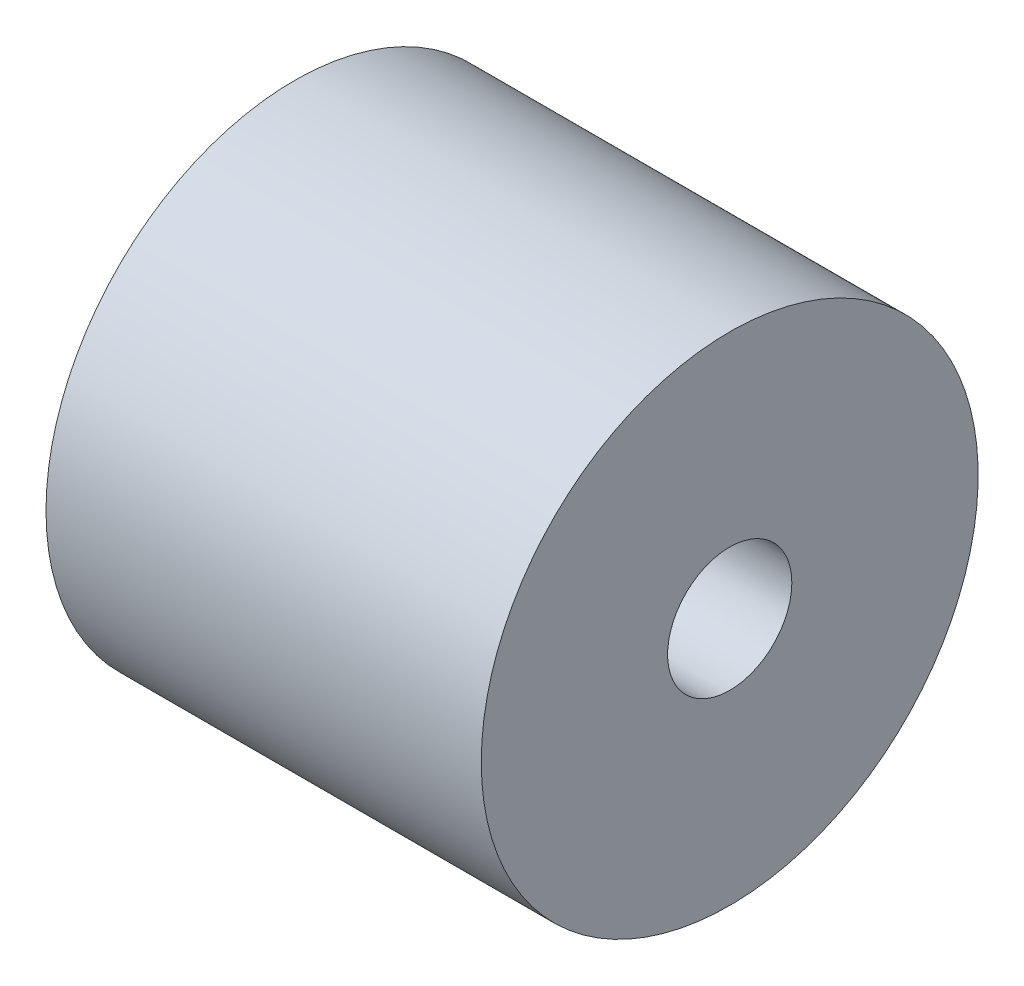
SolidWorks part; units mm, degrees
ref_plane "Front Plane" through (0, 0, 0) normal (0, 0, 1) x (1, 0, 0)
ref_plane "Top Plane" through (0, 0, 0) normal (0, 1, 0) x (1, 0, 0)
ref_plane "Right Plane" through (0, 0, 0) normal (1, 0, 0) x (0, 0, -1)
sketch "Sketch1" plane through (0, 0, 0) normal (1, 0, 0) x (0, 0, -1)
  circle A0 centre (0, 0) radius 3.175
  circle A1 centre (0, 0) radius 6.35
  dimension "D1" = 6.35
  dimension "D2" = 3.175
extrude "Boss-Extrude1" add sketch "Sketch1" along normal blind 11.1252
sketch "Sketch2" plane through (11.1252, 0, 0) normal (1, 0, 0) x (0, 0, -1)
  circle A0 centre (0, 0) radius 3.175
  circle A1 centre (0, 0) radius 1.5875
  circle A2 centre (0, 0) radius 3.175 construction
  dimension "D1" = 3.175
extrude "Boss-Extrude2" add sketch "Sketch2" against normal blind 5.5626
